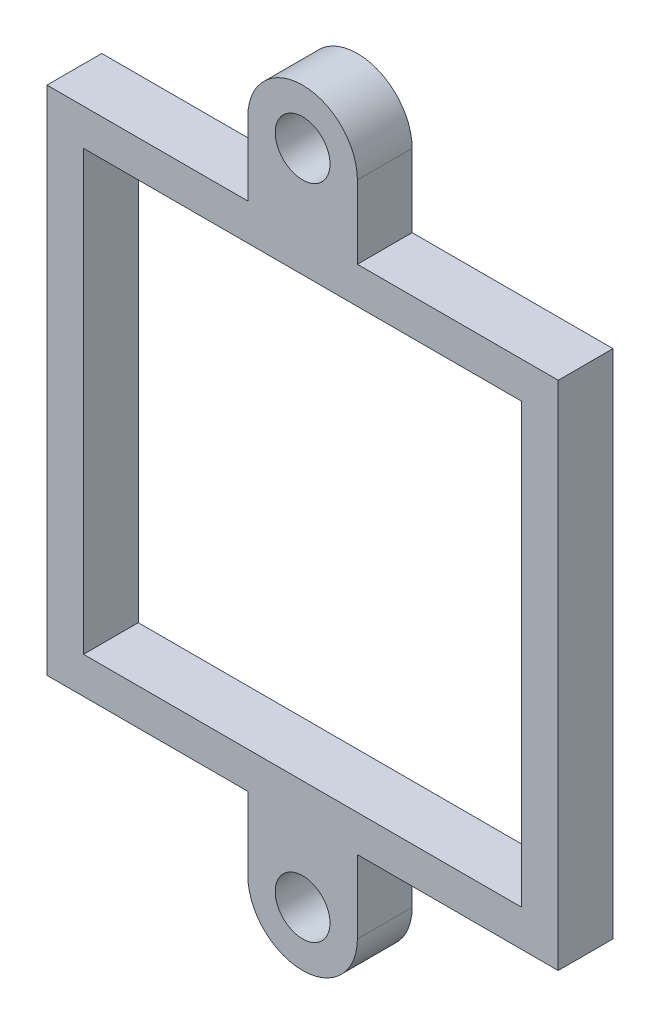
SolidWorks part; units mm, degrees
ref_plane "前视基准面" through (0, 0, 0) normal (0, 0, 1) x (1, 0, 0)
ref_plane "上视基准面" through (0, 0, 0) normal (0, 1, 0) x (1, 0, 0)
ref_plane "右视基准面" through (0, 0, 0) normal (1, 0, 0) x (0, 0, -1)
sketch "草图6" plane through (0, 0, 0) normal (0, 0, 1) x (1, 0, 0)
  line L0 (-7, 7) -> (7, 7)
  line L1 (-6, -6) -> (6, -6)
  line L2 (-6, -6) -> (-6, 6)
  line L3 (-6, 6) -> (6, 6)
  line L4 (6, -6) -> (6, 6)
  line L5 (-6, -6) -> (6, 6) construction
  line L6 (-6, 6) -> (6, -6) construction
  line L7 (7, -7) -> (7, 7)
  line L8 (-7, -7) -> (7, -7)
  line L9 (-7, -7) -> (-7, 7)
  point P0 (0, 0)
  dimension "D1" = 12
  dimension "D3" = 12
  dimension "D2" = 1
extrude "凸台-拉伸3" add sketch "草图6" along normal blind 1.5
sketch "草图7" plane through (0, -7, 0) normal (0, -1, 0) x (1, 0, 0)
  line L0 (-7, 1.5) -> (7, 1.5) construction
  line L1 (-1.5, 0) -> (1.5, 0)
  line L2 (-1.5, 0) -> (-1.5, 1.5)
  line L3 (-1.5, 1.5) -> (1.5, 1.5)
  line L4 (1.5, 0) -> (1.5, 1.5)
  line L5 (-1.5, 0) -> (1.5, 1.5) construction
  line L6 (-1.5, 1.5) -> (1.5, 0) construction
  line L7 (-7, 0) -> (7, 0) construction
  point P0 (0, 0.75)
  dimension "D1" = 3
extrude "凸台-拉伸4" add sketch "草图7" along normal blind 3.5
sketch "草图8" plane through (0, 0, 1.5) normal (0, 0, 1) x (1, 0, 0)
  line L0 (1.5, -10.5) -> (1.5, -7) construction
  line L3 (1.5, -10.5) -> (-1.5, -10.5) construction
  line L4 (-1.5, -10.5) -> (-1.5, -7) construction
  line L5 (1.5, -9) -> (1.5, -10.5)
  line L6 (1.5, -10.5) -> (-1.5, -10.5)
  line L7 (-1.5, -10.5) -> (-1.5, -9)
  circle A0 centre (0, -9) radius 1.5
  point P14 (0, 0)
  line M4 (-1.5, -7) -> (-1.5, -10.5)
  line M5 (-1.5, -10.5) -> (1.5, -10.5)
  line M6 (1.5, -10.5) -> (1.5, -7)
extrude "切除-拉伸3" cut sketch "草图8" against normal blind 4 contours A0 M4 M5 | A0 L6 M6
sketch "草图11" plane through (0, 0, 1.5) normal (0, 0, 1) x (1, 0, 0)
  circle A0 centre (0, -9) radius 0.75
  dimension "D1" = 9
  dimension "D2" = 1.5
extrude "切除-拉伸5" cut sketch "草图11" against normal blind 4
mirror "镜向1" about plane through (0, 0, 0) normal (0, 1, 0) of "切除-拉伸3", "凸台-拉伸4", "切除-拉伸5"
